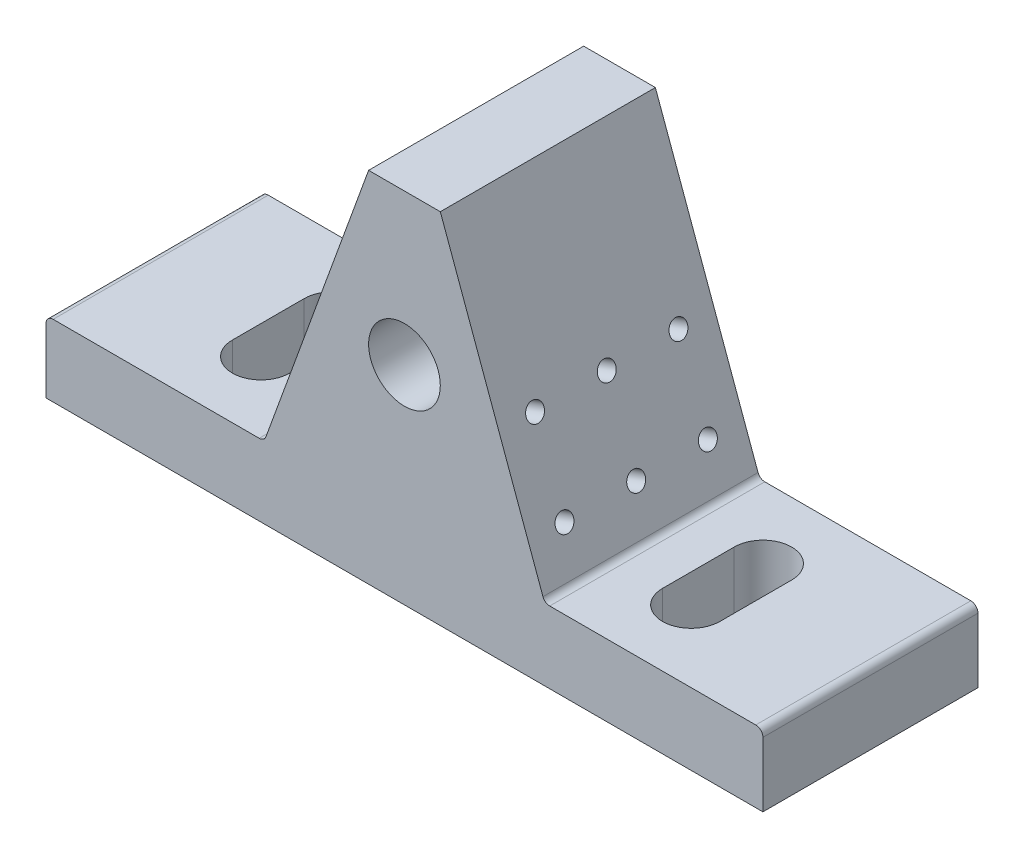
SolidWorks part; units mm, degrees
material "AISI 304"
ref_plane "Front Plane" through (0, 0, 0) normal (0, 0, 1) x (1, 0, 0)
ref_plane "Top Plane" through (0, 0, 0) normal (0, 1, 0) x (1, 0, 0)
ref_plane "Right Plane" through (0, 0, 0) normal (1, 0, 0) x (0, 0, -1)
sketch "Sketch1" plane through (0, 0, 0) normal (0, 0, 1) x (1, 0, 0)
  line L0 (0, 0) -> (0, 50) construction
  line L1 (-50, 0) -> (50, 0)
  line L2 (50, 0) -> (50, 10)
  line L3 (-50, 0) -> (-50, 10)
  line L4 (50, 10) -> (19.5588, 10)
  line L5 (-50, 10) -> (-19.5588, 10)
  line L6 (19.5588, 10) -> (5, 50)
  line L7 (-19.5588, 10) -> (-5, 50)
  line L8 (5, 50) -> (-5, 50)
  dimension "D1" = 110
  dimension "D2" = 10
  dimension "D3" = 50
  dimension "D4" = 10
  dimension "D5" = 100
extrude "Base Extrude" add sketch "Sketch1" along normal mid plane 30
sketch "Sketch2" plane through (0, 10, 0) normal (0, 1, 0) x (1, 0, 0)
  line L0 (30, -5) -> (30, 5) construction
  line L1 (26, -5) -> (26, 5)
  line L2 (34, -5) -> (34, 5)
  line L3 (50, 15) -> (19.5588, 15) construction
  arc A0 (26, -5) -> (34, -5) centre (30, -5) ccw
  arc A1 (34, 5) -> (26, 5) centre (30, 5) ccw
  point P2 (30, 0)
  dimension "D4" = 4
  dimension "D1" = 30
  dimension "D2" = 10
  dimension "D3" = 10
extrude "Slot Cut" cut sketch "Sketch2" against normal through all
mirror "Mirror1" about plane through (0, 0, 0) normal (1, 0, 0) of "Slot Cut"
sketch "Sketch3" plane through (0, 0, 15) normal (0, 0, 1) x (1, 0, 0)
  circle A0 centre (0, 29) radius 5
  dimension "D1" = 10
  dimension "D2" = 29
extrude "Guide hole" cut sketch "Sketch3" against normal through all
hole_wizard "M3x0.5 Tapped Hole3" positions "Sketch11" profile "Sketch10" tap size "M3x0.5" standard "ANSI Metric"
sketch "Sketch11" plane through (20.4848, 7.4559, 0) normal (0.9397, 0.342, 0) x (0, 0, -1)
  line L0 (15, 2.7074) -> (15, 45.2745) construction
  line L1 (15, 27.2511) -> (-15, 27.2511) construction
  point P0 (-10, 21.2511)
  dimension "D1" = 25
  dimension "D2" = 6
sketch "Sketch10" plane through (13.2165, 27.4253, 10) normal (0, 0, 1) x (-0.342, 0.9397, 0)
  line L0 (0, 0) -> (0, 8.2511)
  line L1 (0, 8.2511) -> (1.25, 7.5)
  line L2 (1.25, 7.5) -> (1.25, 0)
  line L5 (1.25, 0) -> (0, 0)
  line L10 (0, 8.2511) -> (-1.25, 7.5) construction
  line L11 (0, -6.35) -> (0, 107.95) construction
  dimension "Tap Drill Dia." = 2.5
  dimension "Tap Drill Depth" = 7.5
  dimension "Drill Angle" = 118
cosmetic thread "Hole Thread1" parameters "D1"=6, "D2"=3
pattern_linear "LPattern1" count 3 spacing 10 along (0, 0, -1) count 2 spacing 12 along (0.342, -0.9397, 0) of "M3x0.5 Tapped Hole3"
fillet "Fillet1" radius 1 4 edges at (-19.5588, 10, 0) (-50, 10, 0) (50, 10, 0) (19.5588, 10, 0)
